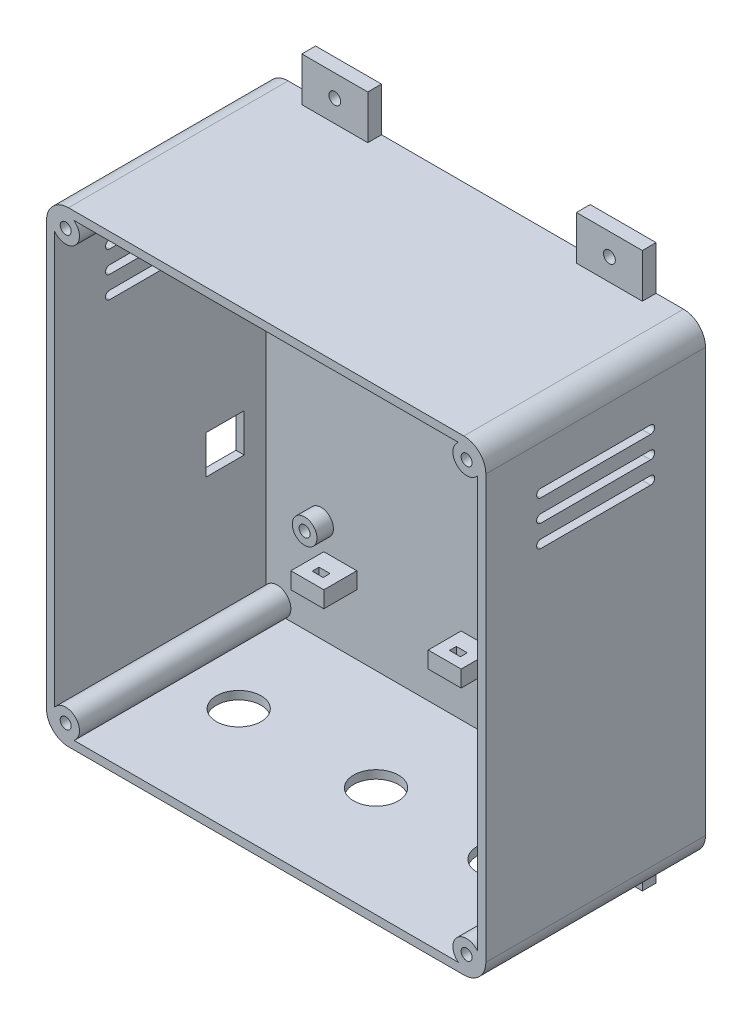
SolidWorks part; units mm, degrees
ref_plane "Front Plane" through (0, 0, 0) normal (0, 0, 1) x (1, 0, 0)
ref_plane "Top Plane" through (0, 0, 0) normal (0, 1, 0) x (1, 0, 0)
ref_plane "Right Plane" through (0, 0, 0) normal (1, 0, 0) x (0, 0, -1)
sketch "Sketch1" plane through (0, 0, 0) normal (0, 0, 1) x (1, 0, 0)
  line L0 (-72, 0) -> (72, 0)
  line L1 (80, 8) -> (80, 162)
  line L2 (72, 170) -> (-72, 170)
  line L3 (-80, 162) -> (-80, 8)
  arc A0 (-80, 8) -> (-72, 0) centre (-72, 8) ccw
  arc A1 (72, 0) -> (80, 8) centre (72, 8) ccw
  arc A2 (80, 162) -> (72, 170) centre (72, 162) ccw
  arc A3 (-72, 170) -> (-80, 162) centre (-72, 162) ccw
extrude "Block" add sketch "Sketch1" along normal blind 80
shell "Shell1" thickness 3
sketch "Sketch2" plane through (0, 0, 0) normal (0, 0, 1) x (1, 0, 0)
  circle A0 centre (-73, 7) radius 5
  circle A1 centre (73, 7) radius 5
  circle A2 centre (-73, 163) radius 5
  circle A3 centre (73, 163) radius 5
extrude "Corner columns" add sketch "Sketch2" along normal blind 80
ref_plane "P1_Front_80" through (0, 0, 80) normal (0, 0, 1) x (1, 0, 0)
sketch "Sketch3" plane through (0, 0, 80) normal (0, 0, 1) x (1, 0, 0)
  circle A0 centre (-73, 7) radius 2
  circle A1 centre (73, 7) radius 2
  circle A2 centre (-73, 163) radius 2
  circle A3 centre (73, 163) radius 2
extrude "Front panel insert holes" cut sketch "Sketch3" against normal blind 7
ref_plane "P2_Front_3" through (0, 0, 3) normal (0, 0, 1) x (1, 0, 0)
sketch "Sketch4" plane through (0, 0, 3) normal (0, 0, 1) x (1, 0, 0)
  circle A0 centre (-57, 40) radius 4.5
  circle A1 centre (57, 40) radius 4.5
  circle A2 centre (-57, 150) radius 4.5
  circle A3 centre (57, 150) radius 4.5
extrude "Plate bosses" add sketch "Sketch4" along normal blind 6
ref_plane "P3_Front_9" through (0, 0, 9) normal (0, 0, 1) x (1, 0, 0)
sketch "Sketch5" plane through (0, 0, 9) normal (0, 0, 1) x (1, 0, 0)
  circle A0 centre (-57, 40) radius 2
  circle A1 centre (57, 40) radius 2
  circle A2 centre (-57, 150) radius 2
  circle A3 centre (57, 150) radius 2
extrude "Plate insert holes" cut sketch "Sketch5" against normal blind 7
sketch "Sketch6" plane through (0, 0, 0) normal (0, 1, 0) x (1, 0, 0)
  circle A0 centre (-50, -40) radius 8.15
  circle A1 centre (0, -40) radius 8.15
  circle A2 centre (45, -40) radius 8.15
extrude "Cable gland holes" cut sketch "Sketch6" along normal blind 4
sketch "Sketch7" plane through (0, 0, 3) normal (0, 0, 1) x (1, 0, 0)
  line L1 (-56, 25) -> (-44, 25)
  line L2 (-56, 25) -> (-56, 31)
  line L3 (-56, 31) -> (-44, 31)
  line L4 (-44, 25) -> (-44, 31)
  line L5 (-56, 25) -> (-44, 31) construction
  line L6 (-56, 31) -> (-44, 25) construction
  line L7 (-6, 25) -> (6, 25)
  line L8 (-6, 25) -> (-6, 31)
  line L9 (-6, 31) -> (6, 31)
  line L10 (6, 25) -> (6, 31)
  line L11 (-6, 25) -> (6, 31) construction
  line L12 (-6, 31) -> (6, 25) construction
  line L13 (39, 25) -> (51, 25)
  line L14 (39, 25) -> (39, 31)
  line L15 (39, 31) -> (51, 31)
  line L16 (51, 25) -> (51, 31)
  line L17 (39, 25) -> (51, 31) construction
  line L18 (39, 31) -> (51, 25) construction
  point P0 (-50, 28)
  point P5 (0, 28)
  point P10 (45, 28)
extrude "Cable tie bars" add sketch "Sketch7" along normal blind 12
ref_plane "P4_Top_24.99" through (0, 24.99, 0) normal (0, 1, 0) x (1, 0, 0)
sketch "Sketch8" plane through (0, 24.99, 0) normal (0, 1, 0) x (1, 0, 0)
  line L1 (-52, -11.25) -> (-48, -11.25)
  line L2 (-52, -11.25) -> (-52, -8.75)
  line L3 (-52, -8.75) -> (-48, -8.75)
  line L4 (-48, -11.25) -> (-48, -8.75)
  line L5 (-52, -11.25) -> (-48, -8.75) construction
  line L6 (-52, -8.75) -> (-48, -11.25) construction
  line L7 (-2, -11.25) -> (2, -11.25)
  line L8 (-2, -11.25) -> (-2, -8.75)
  line L9 (-2, -8.75) -> (2, -8.75)
  line L10 (2, -11.25) -> (2, -8.75)
  line L11 (-2, -11.25) -> (2, -8.75) construction
  line L12 (-2, -8.75) -> (2, -11.25) construction
  line L13 (43, -11.25) -> (47, -11.25)
  line L14 (43, -11.25) -> (43, -8.75)
  line L15 (43, -8.75) -> (47, -8.75)
  line L16 (47, -11.25) -> (47, -8.75)
  line L17 (43, -11.25) -> (47, -8.75) construction
  line L18 (43, -8.75) -> (47, -11.25) construction
  point P0 (-50, -10)
  point P5 (0, -10)
  point P10 (45, -10)
extrude "Cable tie slots" cut sketch "Sketch8" along normal blind 6.02
ref_plane "P5_Right_-80" through (-80, 0, 0) normal (1, 0, 0) x (0, 0, -1)
sketch "Sketch9" plane through (-80, 0, 0) normal (1, 0, 0) x (0, 0, -1)
  line L1 (-25, 55) -> (-11, 55)
  line L2 (-25, 55) -> (-25, 69)
  line L3 (-25, 69) -> (-11, 69)
  line L4 (-11, 55) -> (-11, 69)
  line L5 (-25, 55) -> (-11, 69) construction
  line L6 (-25, 69) -> (-11, 55) construction
  point P0 (-18, 62)
extrude "USB access" cut sketch "Sketch9" along normal blind 4
ref_plane "P6_Right_-80" through (-80, 0, 0) normal (1, 0, 0) x (0, 0, -1)
sketch "Sketch10" plane through (-80, 0, 0) normal (1, 0, 0) x (0, 0, -1)
  line L0 (-20, 130) -> (-60, 130) construction
  line L1 (-20, 128.5) -> (-60, 128.5)
  line L2 (-20, 131.5) -> (-60, 131.5)
  line L3 (-20, 138) -> (-60, 138) construction
  line L4 (-20, 136.5) -> (-60, 136.5)
  line L5 (-20, 139.5) -> (-60, 139.5)
  line L6 (-20, 146) -> (-60, 146) construction
  line L7 (-20, 144.5) -> (-60, 144.5)
  line L8 (-20, 147.5) -> (-60, 147.5)
  arc A0 (-20, 128.5) -> (-20, 131.5) centre (-20, 130) ccw
  arc A1 (-60, 131.5) -> (-60, 128.5) centre (-60, 130) ccw
  arc A2 (-20, 136.5) -> (-20, 139.5) centre (-20, 138) ccw
  arc A3 (-60, 139.5) -> (-60, 136.5) centre (-60, 138) ccw
  arc A4 (-20, 144.5) -> (-20, 147.5) centre (-20, 146) ccw
  arc A5 (-60, 147.5) -> (-60, 144.5) centre (-60, 146) ccw
  point P2 (-40, 130)
  point P7 (-40, 138)
  point P14 (-40, 146)
  point P21 (0, 0)
extrude "Vents left" cut sketch "Sketch10" along normal blind 4
ref_plane "P7_Right_80" through (80, 0, 0) normal (1, 0, 0) x (0, 0, -1)
sketch "Sketch11" plane through (80, 0, 0) normal (1, 0, 0) x (0, 0, -1)
  line L0 (-20, 130) -> (-60, 130) construction
  line L1 (-20, 128.5) -> (-60, 128.5)
  line L2 (-20, 131.5) -> (-60, 131.5)
  line L3 (-20, 138) -> (-60, 138) construction
  line L4 (-20, 136.5) -> (-60, 136.5)
  line L5 (-20, 139.5) -> (-60, 139.5)
  line L6 (-20, 146) -> (-60, 146) construction
  line L7 (-20, 144.5) -> (-60, 144.5)
  line L8 (-20, 147.5) -> (-60, 147.5)
  arc A0 (-20, 128.5) -> (-20, 131.5) centre (-20, 130) ccw
  arc A1 (-60, 131.5) -> (-60, 128.5) centre (-60, 130) ccw
  arc A2 (-20, 136.5) -> (-20, 139.5) centre (-20, 138) ccw
  arc A3 (-60, 139.5) -> (-60, 136.5) centre (-60, 138) ccw
  arc A4 (-20, 144.5) -> (-20, 147.5) centre (-20, 146) ccw
  arc A5 (-60, 147.5) -> (-60, 144.5) centre (-60, 146) ccw
  point P2 (-40, 130)
  point P7 (-40, 138)
  point P14 (-40, 146)
  point P21 (0, 0)
extrude "Vents right" cut sketch "Sketch11" against normal blind 4
sketch "Sketch12" plane through (0, 0, 0) normal (0, 0, 1) x (1, 0, 0)
  circle A0 centre (-40, 130) radius 4.75
  circle A1 centre (40, 130) radius 4.75
extrude "Keyhole heads" cut sketch "Sketch12" along normal blind 4
sketch "Sketch13" plane through (0, 0, 0) normal (0, 0, 1) x (1, 0, 0)
  line L0 (-40, 130) -> (-40, 141) construction
  line L1 (-42.15, 130) -> (-42.15, 141)
  line L2 (-37.85, 130) -> (-37.85, 141)
  line L3 (40, 130) -> (40, 141) construction
  line L4 (37.85, 130) -> (37.85, 141)
  line L5 (42.15, 130) -> (42.15, 141)
  arc A0 (-42.15, 130) -> (-37.85, 130) centre (-40, 130) ccw
  arc A1 (-37.85, 141) -> (-42.15, 141) centre (-40, 141) ccw
  arc A2 (37.85, 130) -> (42.15, 130) centre (40, 130) ccw
  arc A3 (42.15, 141) -> (37.85, 141) centre (40, 141) ccw
  point P2 (-40, 135.5)
  point P7 (40, 135.5)
  point P14 (0, 0)
extrude "Keyhole slots" cut sketch "Sketch13" along normal blind 4
sketch "Sketch14" plane through (0, 0, 0) normal (0, 0, 1) x (1, 0, 0)
  line L1 (-62, -16) -> (-38, -16)
  line L2 (-62, -16) -> (-62, 0)
  line L3 (-62, 0) -> (-38, 0)
  line L4 (-38, -16) -> (-38, 0)
  line L6 (-62, 170) -> (-38, 170)
  line L7 (-62, 170) -> (-62, 186)
  line L8 (-62, 186) -> (-38, 186)
  line L9 (-38, 170) -> (-38, 186)
  line L11 (38, -16) -> (62, -16)
  line L12 (38, -16) -> (38, 0)
  line L13 (38, 0) -> (62, 0)
  line L14 (62, -16) -> (62, 0)
  line L16 (38, 170) -> (62, 170)
  line L17 (38, 170) -> (38, 186)
  line L18 (38, 186) -> (62, 186)
  line L19 (62, 170) -> (62, 186)
extrude "Wall ears" add sketch "Sketch14" along normal blind 5
sketch "Sketch15" plane through (0, 0, 0) normal (0, 0, 1) x (1, 0, 0)
  circle A0 centre (-50, -8) radius 2.15
  circle A1 centre (-50, 178) radius 2.15
  circle A2 centre (50, -8) radius 2.15
  circle A3 centre (50, 178) radius 2.15
extrude "Wall ear screw holes" cut sketch "Sketch15" along normal through all
